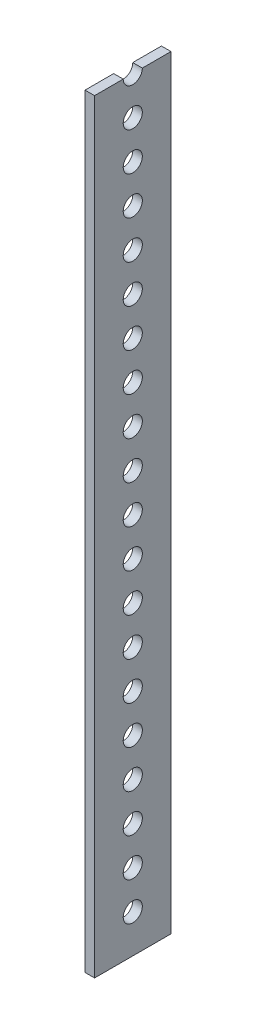
SolidWorks part; units mm, degrees
ref_plane "Front Plane" through (0, 0, 0) normal (0, 0, 1) x (1, 0, 0)
ref_plane "Top Plane" through (0, 0, 0) normal (0, 1, 0) x (1, 0, 0)
ref_plane "Right Plane" through (0, 0, 0) normal (1, 0, 0) x (0, 0, -1)
sketch "Sketch1" plane through (0, 0, 0) normal (1, 0, 0) x (0, 0, -1)
  line L1 (-12.7, -698.5) -> (12.7, -698.5)
  line L2 (-12.7, -698.5) -> (-12.7, 698.5)
  line L3 (-12.7, 698.5) -> (12.7, 698.5)
  line L4 (12.7, -698.5) -> (12.7, 698.5)
  line L5 (-12.7, -698.5) -> (12.7, 698.5) construction
  line L6 (-12.7, 698.5) -> (12.7, -698.5) construction
  circle A0 centre (0, -685.8) radius 3.175
  circle A1 centre (0, -673.1) radius 3.175
  circle A2 centre (0, -660.4) radius 3.175
  circle A3 centre (0, -647.7) radius 3.175
  circle A4 centre (0, -635) radius 3.175
  circle A5 centre (0, -622.3) radius 3.175
  circle A6 centre (0, -609.6) radius 3.175
  circle A7 centre (0, -596.9) radius 3.175
  circle A8 centre (0, -584.2) radius 3.175
  circle A9 centre (0, -571.5) radius 3.175
  circle A10 centre (0, -558.8) radius 3.175
  circle A11 centre (0, -546.1) radius 3.175
  circle A12 centre (0, -533.4) radius 3.175
  circle A13 centre (0, -520.7) radius 3.175
  circle A14 centre (0, -508) radius 3.175
  circle A15 centre (0, -495.3) radius 3.175
  circle A16 centre (0, -482.6) radius 3.175
  circle A17 centre (0, -469.9) radius 3.175
  circle A18 centre (0, -457.2) radius 3.175
  circle A19 centre (0, -444.5) radius 3.175
  circle A20 centre (0, -431.8) radius 3.175
  circle A21 centre (0, -419.1) radius 3.175
  circle A22 centre (0, -406.4) radius 3.175
  circle A23 centre (0, -393.7) radius 3.175
  circle A24 centre (0, -381) radius 3.175
  circle A25 centre (0, -368.3) radius 3.175
  circle A26 centre (0, -355.6) radius 3.175
  circle A27 centre (0, -342.9) radius 3.175
  circle A28 centre (0, -330.2) radius 3.175
  circle A29 centre (0, -317.5) radius 3.175
  circle A30 centre (0, -304.8) radius 3.175
  circle A31 centre (0, -292.1) radius 3.175
  circle A32 centre (0, -279.4) radius 3.175
  circle A33 centre (0, -266.7) radius 3.175
  circle A34 centre (0, -254) radius 3.175
  circle A35 centre (0, -241.3) radius 3.175
  circle A36 centre (0, -228.6) radius 3.175
  circle A37 centre (0, -215.9) radius 3.175
  circle A38 centre (0, -203.2) radius 3.175
  circle A39 centre (0, -190.5) radius 3.175
  circle A40 centre (0, -177.8) radius 3.175
  circle A41 centre (0, -165.1) radius 3.175
  circle A42 centre (0, -152.4) radius 3.175
  circle A43 centre (0, -139.7) radius 3.175
  circle A44 centre (0, -127) radius 3.175
  circle A45 centre (0, -114.3) radius 3.175
  circle A46 centre (0, -101.6) radius 3.175
  circle A47 centre (0, -88.9) radius 3.175
  circle A48 centre (0, -76.2) radius 3.175
  circle A49 centre (0, -63.5) radius 3.175
  circle A50 centre (0, -50.8) radius 3.175
  circle A51 centre (0, -38.1) radius 3.175
  circle A52 centre (0, -25.4) radius 3.175
  circle A53 centre (0, -12.7) radius 3.175
  circle A54 centre (0, 0) radius 3.175
  circle A55 centre (0, 12.7) radius 3.175
  circle A56 centre (0, 25.4) radius 3.175
  circle A57 centre (0, 38.1) radius 3.175
  circle A58 centre (0, 50.8) radius 3.175
  circle A59 centre (0, 63.5) radius 3.175
  circle A60 centre (0, 76.2) radius 3.175
  circle A61 centre (0, 88.9) radius 3.175
  circle A62 centre (0, 101.6) radius 3.175
  circle A63 centre (0, 114.3) radius 3.175
  circle A64 centre (0, 127) radius 3.175
  circle A65 centre (0, 139.7) radius 3.175
  circle A66 centre (0, 152.4) radius 3.175
  circle A67 centre (0, 165.1) radius 3.175
  circle A68 centre (0, 177.8) radius 3.175
  circle A69 centre (0, 190.5) radius 3.175
  circle A70 centre (0, 203.2) radius 3.175
  circle A71 centre (0, 215.9) radius 3.175
  circle A72 centre (0, 228.6) radius 3.175
  circle A73 centre (0, 241.3) radius 3.175
  circle A74 centre (0, 254) radius 3.175
  circle A75 centre (0, 266.7) radius 3.175
  circle A76 centre (0, 279.4) radius 3.175
  circle A77 centre (0, 292.1) radius 3.175
  circle A78 centre (0, 304.8) radius 3.175
  circle A79 centre (0, 317.5) radius 3.175
  circle A80 centre (0, 330.2) radius 3.175
  circle A81 centre (0, 342.9) radius 3.175
  circle A82 centre (0, 355.6) radius 3.175
  circle A83 centre (0, 368.3) radius 3.175
  circle A84 centre (0, 381) radius 3.175
  circle A85 centre (0, 393.7) radius 3.175
  circle A86 centre (0, 406.4) radius 3.175
  circle A87 centre (0, 419.1) radius 3.175
  circle A88 centre (0, 431.8) radius 3.175
  circle A89 centre (0, 444.5) radius 3.175
  circle A90 centre (0, 457.2) radius 3.175
  circle A91 centre (0, 469.9) radius 3.175
  circle A92 centre (0, 482.6) radius 3.175
  circle A93 centre (0, 495.3) radius 3.175
  circle A94 centre (0, 508) radius 3.175
  circle A95 centre (0, 520.7) radius 3.175
  circle A96 centre (0, 533.4) radius 3.175
  circle A97 centre (0, 546.1) radius 3.175
  circle A98 centre (0, 558.8) radius 3.175
  circle A99 centre (0, 571.5) radius 3.175
  circle A100 centre (0, 584.2) radius 3.175
  circle A101 centre (0, 596.9) radius 3.175
  circle A102 centre (0, 609.6) radius 3.175
  circle A103 centre (0, 622.3) radius 3.175
  circle A104 centre (0, 635) radius 3.175
  circle A105 centre (0, 647.7) radius 3.175
  circle A106 centre (0, 660.4) radius 3.175
  circle A107 centre (0, 673.1) radius 3.175
  circle A108 centre (0, 685.8) radius 3.175
  point P0 (0, 0)
  dimension "D1" = 109
extrude "Boss-Extrude1" add sketch "Sketch1" along normal blind 3.175
sketch "Sketch2" plane through (3.175, 0, 0) normal (1, 0, 0) x (0, 0, -1)
  line L0 (12.7, -698.5) -> (12.7, 698.5) construction
  line L1 (-12.7, 698.5) -> (12.7, 698.5)
  line L2 (-12.7, 698.5) -> (-12.7, -444.5)
  line L3 (-12.7, -444.5) -> (12.7, -444.5)
  line L4 (12.7, 698.5) -> (12.7, -444.5)
extrude "Cut-Extrude1" cut sketch "Sketch2" against normal through all both and the other way through all
